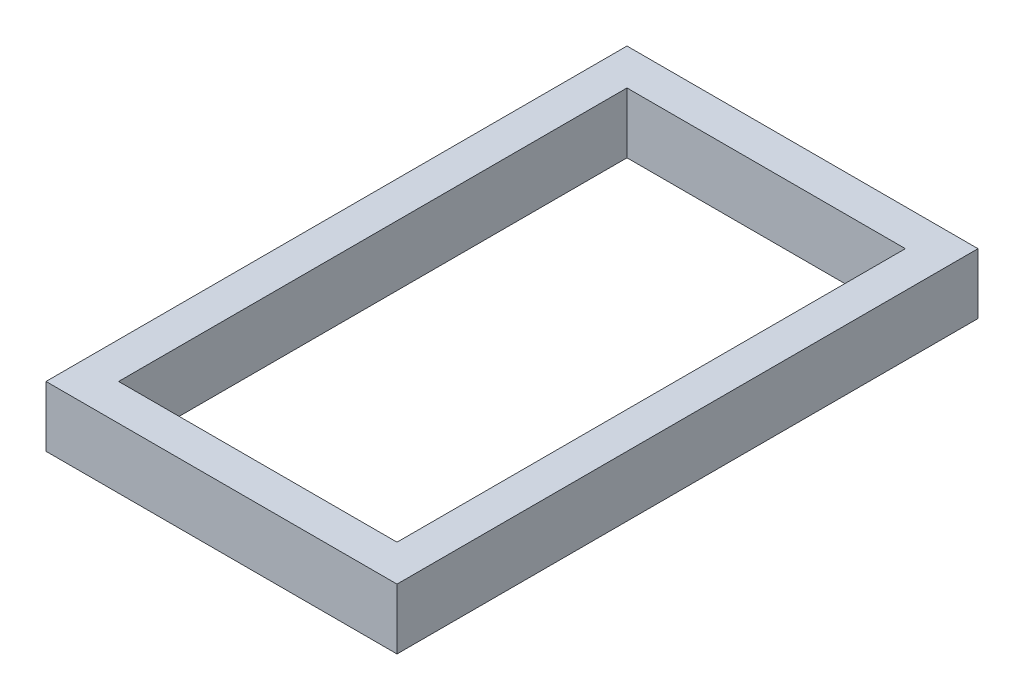
SolidWorks part; units mm, degrees
ref_plane "Front Plane" through (0, 0, 0) normal (0, 0, 1) x (1, 0, 0)
ref_plane "Top Plane" through (0, 0, 0) normal (0, 1, 0) x (1, 0, 0)
ref_plane "Right Plane" through (0, 0, 0) normal (1, 0, 0) x (0, 0, -1)
sketch "Sketch1" plane through (0, 0, 0) normal (0, 1, 0) x (1, 0, 0)
  line L0 (-14.5, -24) -> (-14.5, 24)
  line L1 (-11.5, -21) -> (11.5, -21)
  line L2 (-11.5, -21) -> (-11.5, 21)
  line L3 (-11.5, 21) -> (11.5, 21)
  line L4 (11.5, -21) -> (11.5, 21)
  line L5 (-11.5, -21) -> (11.5, 21) construction
  line L6 (-11.5, 21) -> (11.5, -21) construction
  line L7 (-14.5, 24) -> (14.5, 24)
  line L8 (14.5, -24) -> (14.5, 24)
  line L9 (-14.5, -24) -> (14.5, -24)
  point P0 (0, 0)
  dimension "D1" = 23
  dimension "D2" = 42
  dimension "D3" = 3
extrude "Boss-Extrude1" add sketch "Sketch1" along normal blind 5
